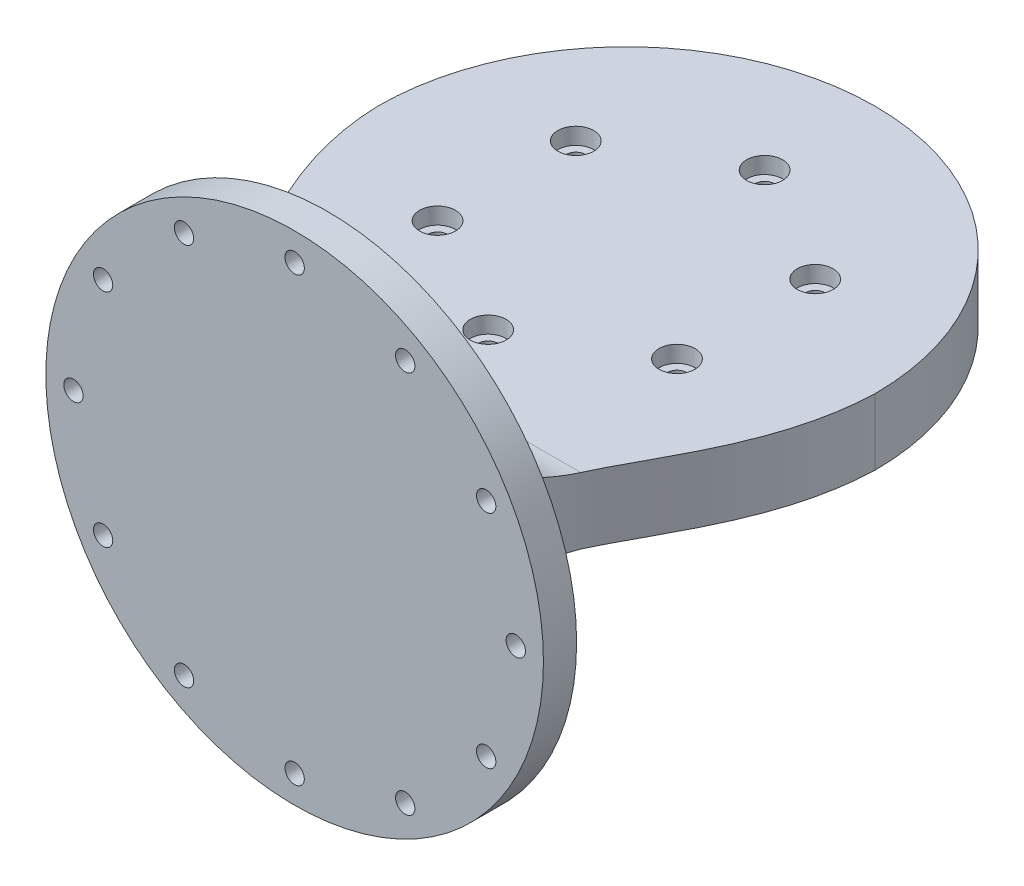
SolidWorks part; units mm, degrees
ref_plane "Front Plane" through (0, 0, 0) normal (0, 0, 1) x (1, 0, 0)
ref_plane "Top Plane" through (0, 0, 0) normal (0, 1, 0) x (1, 0, 0)
ref_plane "Right Plane" through (0, 0, 0) normal (1, 0, 0) x (0, 0, -1)
sketch "Sketch1" plane through (0, 0, 0) normal (0, 1, 0) x (1, 0, 0)
  circle A0 centre (0, 0) radius 45
  dimension "D1" = 90
extrude "Boss-Extrude1" add sketch "Sketch1" along normal blind 12
sketch "Sketch2" plane through (0, 0, 0) normal (0, -1, 0) x (1, 0, 0)
  circle A0 centre (0, 0) radius 35
  dimension "D1" = 70
extrude "Cut-Extrude1" cut sketch "Sketch2" against normal blind 6
sketch "Sketch3" plane through (0, 12, 0) normal (0, 1, 0) x (1, 0, 0)
  line L0 (0, 0) -> (0, -25) construction
  circle A0 centre (0, 0) radius 25 construction
  circle A1 centre (0, -25) radius 1.75
  circle A2 centre (-21.6506, -12.5) radius 1.75
  circle A3 centre (-21.6506, 12.5) radius 1.75
  circle A4 centre (0, 25) radius 1.75
  circle A5 centre (21.6506, 12.5) radius 1.75
  circle A6 centre (21.6506, -12.5) radius 1.75
  point P17 (0, 0)
  dimension "D1" = 50
  dimension "D2" = 3.5
  dimension "D3" = 6
extrude "Cut-Extrude2" cut sketch "Sketch3" against normal through all
sketch "Sketch4" plane through (0, 12, 0) normal (0, 1, 0) x (1, 0, 0)
  circle A0 centre (0, 25) radius 3.25
  circle A1 centre (21.6506, 12.5) radius 3.25
  circle A2 centre (21.6506, -12.5) radius 3.25
  circle A3 centre (0, -25) radius 3.25
  circle A4 centre (-21.6506, -12.5) radius 3.25
  circle A5 centre (-21.6506, 12.5) radius 3.25
  point P15 (0, 0)
  dimension "D1" = 6.5
  dimension "D2" = 6
extrude "Cut-Extrude3" cut sketch "Sketch4" against normal blind 3
sketch "Sketch5" plane through (0, 12, 0) normal (0, 1, 0) x (1, 0, 0)
  line L0 (-45, 0) -> (45, 0) construction
  line L1 (0, 0) -> (0, -45) construction
  line L2 (-45, 0) -> (-45, -60)
  line L3 (-45, -60) -> (45, -60)
  line L4 (45, -60) -> (45, 0)
  circle A0 centre (0, 0) radius 45 construction
  arc A1 (-45, 0) -> (45, 0) centre (0, 0) ccw
  dimension "D1" = 60
extrude "Boss-Extrude3" add sketch "Sketch5" against normal blind 12
sketch "Sketch10" plane through (0, 0, 60) normal (0, 0, 1) x (1, 0, 0)
  line L0 (0, 12) -> (0, 0) construction
  line L1 (-45, 12) -> (45, 12) construction
  line L2 (-45, 0) -> (45, 0) construction
  circle A0 centre (0, 0) radius 45
extrude "Boss-Extrude5" add sketch "Sketch10" against normal blind 6
sketch "Sketch11" plane through (0, 0, 60) normal (0, 0, 1) x (1, 0, 0)
  line L0 (0, 0) -> (48.955, 0) construction
  circle A0 centre (0, 0) radius 40 construction
  circle A1 centre (40, 0) radius 1.75
  circle A2 centre (34.641, -20) radius 1.75
  circle A3 centre (20, -34.641) radius 1.75
  circle A4 centre (0, -40) radius 1.75
  circle A5 centre (-20, -34.641) radius 1.75
  circle A6 centre (-34.641, -20) radius 1.75
  circle A7 centre (-40, 0) radius 1.75
  circle A8 centre (-34.641, 20) radius 1.75
  circle A9 centre (-20, 34.641) radius 1.75
  circle A10 centre (0, 40) radius 1.75
  circle A11 centre (20, 34.641) radius 1.75
  circle A12 centre (34.641, 20) radius 1.75
  point P30 (0, 0)
  dimension "D1" = 80
  dimension "D2" = 3.5
  dimension "D3" = 12
sketch "Sketch14" plane through (0, 0, 0) normal (0, -1, 0) x (1, 0, 0)
  line L1 (45, 0) -> (44.1165, 28.3271) construction
  line L2 (44.1165, 28.3271) -> (18.578, 44.1158) construction
  line L3 (18.578, 44.1158) -> (33.2475, 54) construction
  line L4 (-45, 54) -> (45, 54) construction
  line L6 (45, 0) -> (45, 54)
  line L7 (45, 54) -> (33.2475, 54)
  line L8 (0, 0) -> (0, 60) construction
  line L9 (-45, 0) -> (-44.1165, 28.3271) construction
  line L10 (-44.1165, 28.3271) -> (-18.578, 44.1158) construction
  line L11 (-18.578, 44.1158) -> (-33.2475, 54) construction
  line L12 (-45, 54) -> (-33.2475, 54)
  line L13 (-45, 0) -> (-45, 54)
  circle A0 centre (0, 0) radius 45 construction
  spline S0 degree 3 poles (45, 0) (44.1165, 28.3271) (18.578, 44.1158) (33.2475, 54) knots 0 0 0 0 1 1 1 1
  spline S1 degree 3 poles (-45, 0) (-44.1165, 28.3271) (-18.578, 44.1158) (-33.2475, 54) knots 0 0 0 0 1 1 1 1
  dimension "D1" = 90
sketch "Sketch17" plane through (45, 0, 0) normal (1, 0, 0) x (0, 0, -1)
  line L0 (45, 6) -> (-60, 6) construction
  line L1 (-54, 12) -> (-39.0023, 12)
  line L2 (-54, 26.9977) -> (-54, 12)
  line L3 (45, 0) -> (45, 12) construction
  line L4 (-60, 40) -> (-60, -40) construction
  line L6 (-54, 0) -> (0, 0) construction
  line L7 (-54, -45) -> (-54, 0) construction
  line L8 (-54, -14.9977) -> (-54, 0)
  line L9 (-54, 0) -> (-39.0023, 0)
  arc A0 (-39.0023, 0) -> (-54, -14.9977) centre (-39.0023, -14.9977) ccw
  arc A1 (-39.0023, 12) -> (-54, 26.9977) centre (-39.0023, 26.9977) cw
  line M2 (0, 12) -> (-60, 12)
  line M5 (-54, 0) -> (0, 0)
extrude "Boss-Extrude7" add sketch "Sketch17" against normal through all contours A1 L2 M2 | A0 L8 M5
extrude "Cut-Extrude14" cut sketch "Sketch14" against normal through all both and the other way through all
extrude "Cut-Extrude15" cut sketch "Sketch11" against normal up to next
sketch "Sketch18" plane through (0, 0, 54) normal (0, 0, -1) x (-1, 0, 0)
  circle A0 centre (0, 40) radius 3.25
  circle A1 centre (20, 34.641) radius 3.25
  circle A2 centre (34.641, 20) radius 3.25
  circle A3 centre (40, 0) radius 3.25
  circle A4 centre (34.641, -20) radius 3.25
  circle A5 centre (20, -34.641) radius 3.25
  circle A6 centre (0, -40) radius 3.25
  circle A7 centre (-20, -34.641) radius 3.25
  circle A8 centre (-34.641, -20) radius 3.25
  circle A9 centre (-40, 0) radius 3.25
  circle A10 centre (-34.641, 20) radius 3.25
  circle A11 centre (-20, 34.641) radius 3.25
  point P27 (0, 0)
  dimension "D1" = 6.5
  dimension "D2" = 12
extrude "Cut-Extrude16" cut sketch "Sketch18" against normal blind 3
sketch "Sketch19" plane through (0, 0, 54) normal (0, 0, -1) x (-1, 0, 0)
  line L0 (45, 0) -> (-45, 0) construction
  line L1 (-45, 0) -> (45, 0) construction
  line L2 (-45, 0) -> (-45, 12) construction
  line L3 (0, 0) -> (0, 54.4625) construction
  circle A0 centre (-34.641, 20) radius 6
  circle A1 centre (34.641, 20) radius 6
  circle A2 centre (-34.641, -20) radius 6
  circle A3 centre (34.641, -20) radius 6
  dimension "D1" = 12
extrude "Cut-Extrude17" cut sketch "Sketch19" along normal through all
sketch "Sketch20" plane through (0, 0, 60) normal (0, 0, 1) x (1, 0, 0)
  line L0 (-45, 12) -> (-43.3705, 12) construction
  line L1 (-43.3705, 12) -> (-45, 12)
  line L2 (-45, 12) -> (-45, 0)
  line L3 (0, 0) -> (0, 45) construction
  line L4 (45, 12) -> (45, 0)
  line L5 (43.3705, 12) -> (45, 12)
  arc A0 (-45, 0) -> (-43.3705, 12) centre (0, 0) cw
  arc A1 (43.3705, 12) -> (-43.3705, 12) centre (0, 0) ccw construction
  arc A2 (45, 0) -> (43.3705, 12) centre (0, 0) ccw
extrude "Cut-Extrude18" cut sketch "Sketch20" against normal up to next
